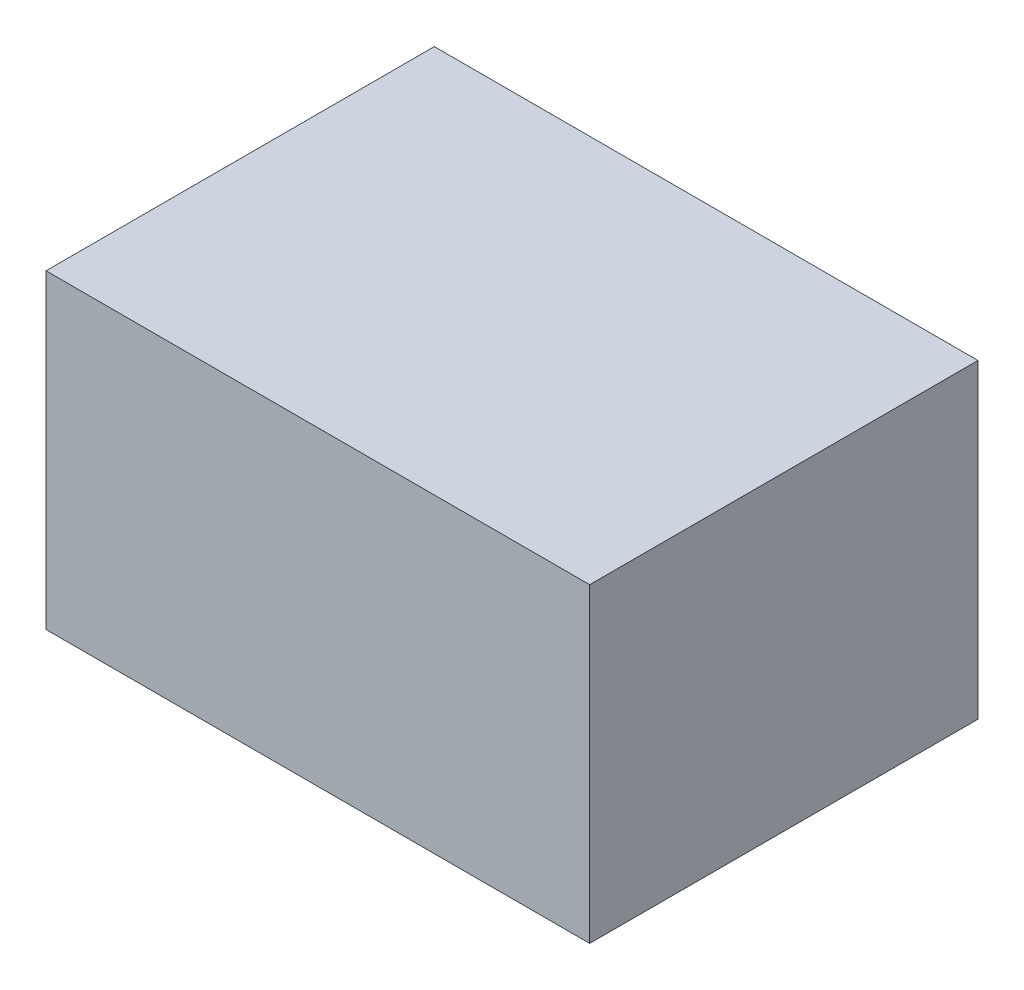
SolidWorks part; units mm, degrees
ref_plane "Front Plane" through (0, 0, 0) normal (0, 0, 1) x (1, 0, 0)
ref_plane "Top Plane" through (0, 0, 0) normal (0, 1, 0) x (1, 0, 0)
ref_plane "Right Plane" through (0, 0, 0) normal (1, 0, 0) x (0, 0, -1)
sketch "Sketch1" plane through (0, 0, 0) normal (0, 1, 0) x (1, 0, 0)
  line L1 (0, 0) -> (140, 0)
  line L2 (0, 0) -> (0, 100)
  line L3 (0, 100) -> (140, 100)
  line L4 (140, 0) -> (140, 100)
extrude "Boss-Extrude1" add sketch "Sketch1" along normal blind 80
